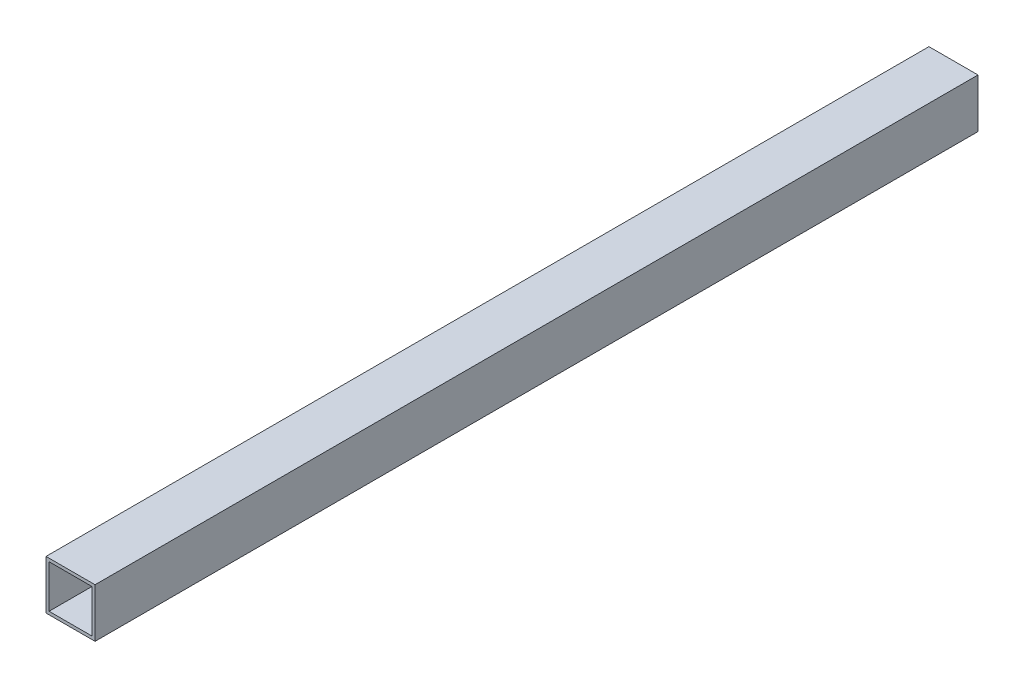
SolidWorks part; units mm, degrees
ref_plane "Front Plane" through (0, 0, 0) normal (0, 0, 1) x (1, 0, 0)
ref_plane "Top Plane" through (0, 0, 0) normal (0, 1, 0) x (1, 0, 0)
ref_plane "Right Plane" through (0, 0, 0) normal (1, 0, 0) x (0, 0, -1)
sketch "Sketch1" plane through (0, 0, 0) normal (0, 1, 0) x (1, 0, 0)
  line L1 (-12.7, -228.6) -> (12.7, -228.6)
  line L2 (-12.7, -228.6) -> (-12.7, 228.6)
  line L3 (-12.7, 228.6) -> (12.7, 228.6)
  line L4 (12.7, -228.6) -> (12.7, 228.6)
  line L5 (-12.7, -228.6) -> (12.7, 228.6) construction
  line L6 (-12.7, 228.6) -> (12.7, -228.6) construction
  point P0 (0, 0)
  dimension "D1" = 457.2
  dimension "D2" = 25.4
extrude "Boss-Extrude1" add sketch "Sketch1" along normal blind 25.4
sketch "Sketch3" plane through (0, 0, 228.6) normal (0, 0, 1) x (1, 0, 0)
  line L0 (12.7, 25.4) -> (12.7, 0) construction
  line L1 (-11.1125, 1.5875) -> (11.1125, 1.5875)
  line L2 (-11.1125, 1.5875) -> (-11.1125, 23.8125)
  line L3 (-11.1125, 23.8125) -> (11.1125, 23.8125)
  line L4 (11.1125, 1.5875) -> (11.1125, 23.8125)
  line L5 (-11.1125, 1.5875) -> (11.1125, 23.8125) construction
  line L6 (-11.1125, 23.8125) -> (11.1125, 1.5875) construction
  line L7 (-12.7, 25.4) -> (-12.7, 0) construction
  line L8 (-12.7, 0) -> (12.7, 0) construction
  line L9 (-12.7, 25.4) -> (12.7, 25.4) construction
  point P0 (0, 12.7)
  dimension "D1" = 1.5875
  dimension "D2" = 1.5875
  dimension "D3" = 1.5875
  dimension "D4" = 1.5875
extrude "Cut-Extrude2" cut sketch "Sketch3" against normal blind 457.2
